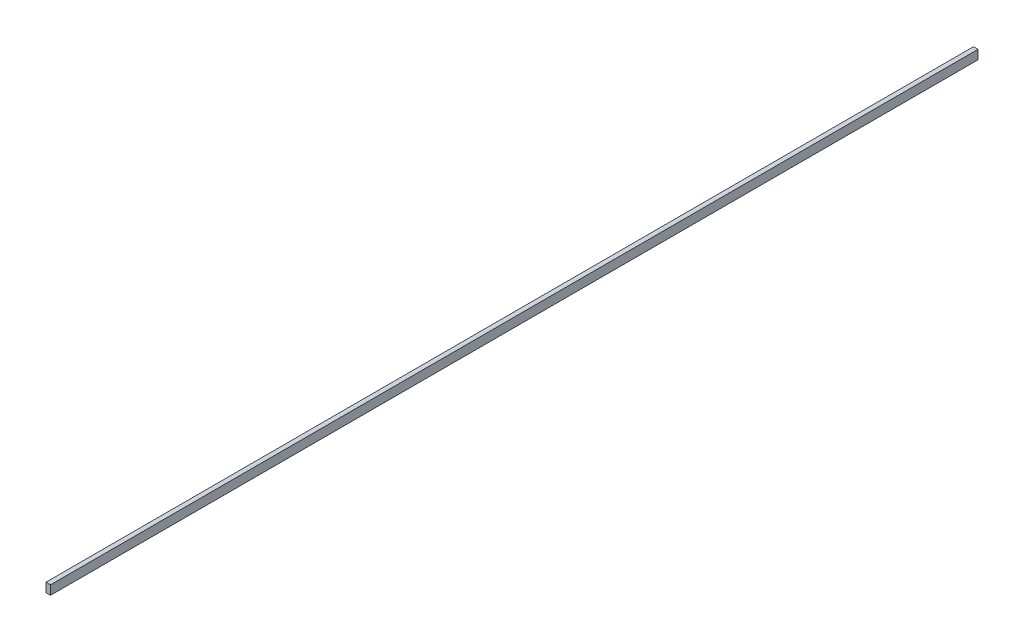
SolidWorks part; units mm, degrees
material "Acrylic (Medium-high impact)"
ref_plane "Front Plane" through (0, 0, 0) normal (0, 0, 1) x (1, 0, 0)
ref_plane "Top Plane" through (0, 0, 0) normal (0, 1, 0) x (1, 0, 0)
ref_plane "Right Plane" through (0, 0, 0) normal (1, 0, 0) x (0, 0, -1)
sketch "Sketch1" plane through (0, 0, 0) normal (0, 0, 1) x (1, 0, 0)
  line L0 (0, 10) -> (0, 0)
  line L1 (0, 0) -> (5, 0)
  line L10 (5, 5) -> (5, 10)
  line L11 (5, 10) -> (0, 10)
  line L12 (5, 5) -> (5, 0)
  dimension "D2" = 10
  dimension "D4" = 5
extrude "Boss-Extrude1" add sketch "Sketch1" along normal blind 1020
